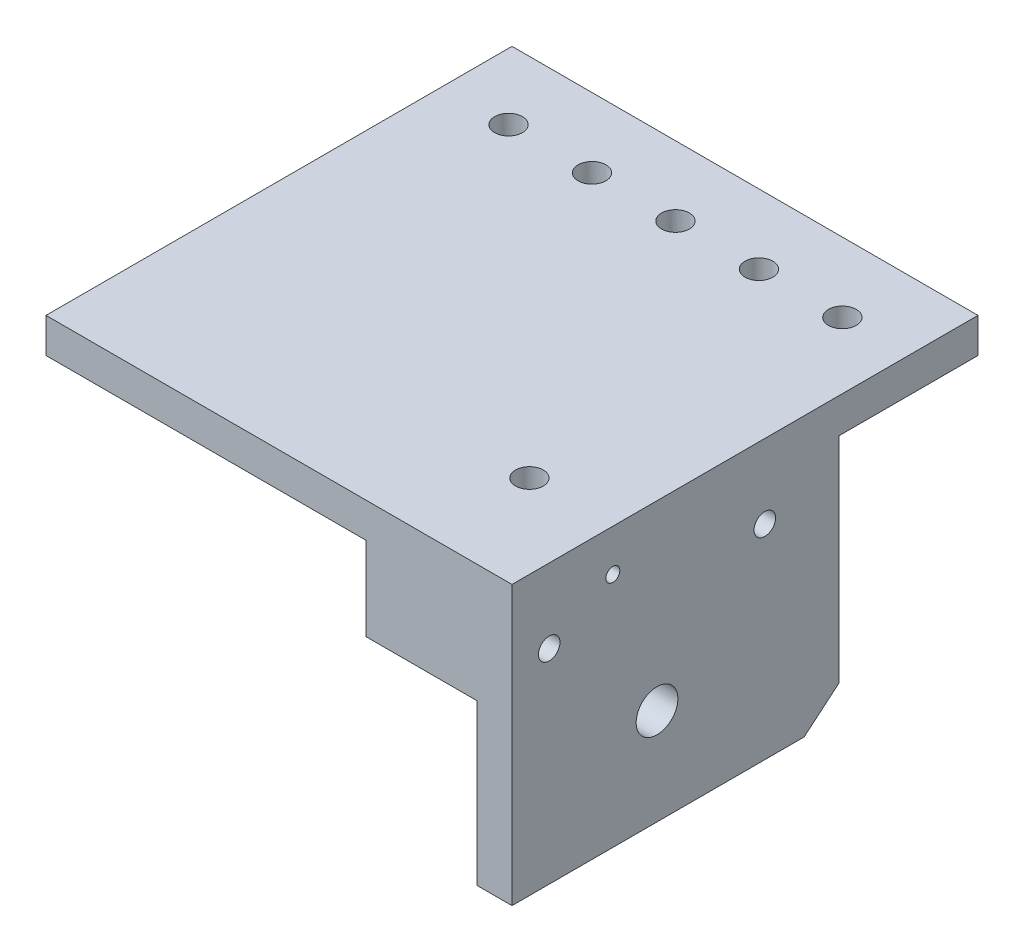
SolidWorks part; units mm, degrees
ref_plane "Front Plane" through (0, 0, 0) normal (0, 0, 1) x (1, 0, 0)
ref_plane "Top Plane" through (0, 0, 0) normal (0, 1, 0) x (1, 0, 0)
ref_plane "Right Plane" through (0, 0, 0) normal (1, 0, 0) x (0, 0, -1)
sketch "Sketch1" plane through (0, 0, 0) normal (1, 0, 0) x (0, 0, -1)
  line L0 (-15, 15) -> (-15, -25)
  line L1 (-10, -10) -> (10, -10) construction
  line L2 (-10, -10) -> (-10, 10)
  line L3 (-10, 10) -> (10, 10)
  line L4 (10, -10) -> (10, 10) construction
  line L5 (-10, -10) -> (10, 10) construction
  line L6 (-10, 10) -> (10, -10) construction
  line L7 (-15, 15) -> (10, 15)
  line L8 (10, 15) -> (10, 10)
  line L9 (-15, -25) -> (-10, -20.8045)
  line L10 (-10, -20.8045) -> (-10, -10)
  point P0 (0, 0)
  dimension "D1" = 20
  dimension "D2" = 5
  dimension "D3" = 5
  dimension "D4" = 40
  dimension "D5" = 50
extrude "Boss-Extrude1" add sketch "Sketch1" along normal blind 50
sketch "Sketch2" plane through (50, 0, 0) normal (1, 0, 0) x (0, 0, -1)
  line L0 (-15, -11.9459) -> (-10, -7.7504)
  line L6 (10, 10) -> (10, 15)
  line L7 (10, 15) -> (-15, 15)
  line L8 (-15, 15) -> (-15, -25)
  line L9 (-15, -25) -> (-10, -20.8045)
  line L10 (-10, -20.8045) -> (-10, 10)
  line L11 (-10, 10) -> (10, 10)
  line L12 (10, 10) -> (10, 15)
  line L13 (10, 15) -> (-15, 15)
  line L14 (-15, 15) -> (-15, -25)
  line L15 (-15, -25) -> (-10, -20.8045)
  line L16 (-10, -20.8045) -> (-10, 10)
  line L17 (-10, 10) -> (10, 10)
  line M8 (10, 10) -> (10, 15)
  line M9 (10, 15) -> (-15, 15)
  line M10 (-15, 15) -> (-15, -25)
  line M12 (-10, -20.8045) -> (-10, 10)
  line M13 (-10, 10) -> (10, 10)
  dimension "D2" = 10
  dimension "D1" = 0
extrude "Boss-Extrude2" add sketch "Sketch2" along normal blind 12 contours L0 M10 M12 M13 M8 M9
sketch "Sketch4" plane through (62, 0, 0) normal (1, 0, 0) x (0, 0, -1)
  line L4 (-10, -7.7504) -> (-15, -11.9459)
  line L5 (-15, -11.9459) -> (-15, -25)
  line L6 (-15, -25) -> (-10, -20.8045)
  line L7 (-10, -20.8045) -> (-10, -7.7504)
  line L8 (-10, -7.7504) -> (-15, -11.9459)
  line L9 (-15, -11.9459) -> (-15, -25)
  line L10 (-15, -25) -> (-10, -20.8045)
  line L11 (-10, -20.8045) -> (-10, -7.7504)
  line L14 (-15, 15) -> (-15, -11.9459)
  line L15 (-15, -11.9459) -> (-10, -7.7504)
  line L16 (-10, -7.7504) -> (-10, 10)
  line L17 (-10, 10) -> (10, 10)
  line L18 (10, 10) -> (10, 15)
  line L19 (10, 15) -> (-15, 15)
  line L20 (-15, 15) -> (-15, -11.9459)
  line L21 (-15, -11.9459) -> (-10, -7.7504)
  line L22 (-10, -7.7504) -> (-10, 10)
  line L23 (-10, 10) -> (10, 10)
  line L24 (10, 10) -> (10, 15)
  line L25 (10, 15) -> (-15, 15)
  line M11 (-15, 15) -> (-15, -11.9459)
  line M12 (-15, -11.9459) -> (-10, -7.7504)
  line M13 (-10, -7.7504) -> (-10, 10)
  line M14 (-10, 10) -> (10, 10)
  line M15 (10, 10) -> (10, 15)
  line M16 (10, 15) -> (-15, 15)
  dimension "D1" = 0
  dimension "D2" = 0
extrude "Boss-Extrude3" add sketch "Sketch4" along normal blind 5 contours M16 M11 M12 M13 M14 M15 | L10 L11 L9 M12
sketch "Sketch5" plane through (0, 0, 15) normal (0, 0, 1) x (1, 0, 0)
  line L0 (67, 15) -> (67, -25) construction
  line L1 (0, 15) -> (67, 15)
  line L2 (0, 15) -> (0, 10)
  line L3 (0, 10) -> (67, 10)
  line L4 (67, 15) -> (67, 10)
  line L6 (62, -25) -> (67, -25)
  line L7 (62, -25) -> (62, 10)
  line L8 (62, 10) -> (67, 10)
  line L9 (67, -25) -> (67, 10)
  line L10 (46, 10) -> (62, 10)
  line L11 (46, 10) -> (46, -2)
  line L12 (46, -2) -> (62, -2)
  line L13 (62, 10) -> (62, -2)
  line M7 (0, 15) -> (0, -25)
  line M11 (62, -11.9459) -> (62, -25)
  line M12 (62, -25) -> (67, -25)
  line M13 (67, -25) -> (67, 15)
  line M14 (67, 15) -> (0, 15)
  dimension "D1" = 5
  dimension "D2" = 12
  dimension "D3" = 16
extrude "Boss-Extrude4" add sketch "Sketch5" along normal blind 42 contours L3 M7 M13 M14 | L11 L12 L7 L3 | L7 L3 M11 M12 M13
sketch "Sketch6" plane through (67, 0, 0) normal (1, 0, 0) x (0, 0, -1)
  line L0 (-57, -25) -> (-57, 15) construction
  line L1 (-57, -25) -> (-15, -25) construction
  circle A0 centre (-36.15, -11.15) radius 3
  dimension "D1" = 20.85
  dimension "D2" = 6
  dimension "D3" = 13.85
extrude "Cut-Extrude1" cut sketch "Sketch6" against normal through all
sketch "Sketch7" plane through (62, 0, 0) normal (-1, 0, 0) x (0, 0, 1)
  circle A0 centre (36.15, -11.15) radius 12
  dimension "D1" = 24
extrude "Cut-Extrude2" cut sketch "Sketch7" along normal through all from offset 14
sketch "Sketch8" plane through (67, 0, 0) normal (1, 0, 0) x (0, 0, -1)
  line L1 (-20.65, -26.65) -> (-51.65, -26.65) construction
  line L2 (-20.65, -26.65) -> (-20.65, 4.35) construction
  line L3 (-20.65, 4.35) -> (-51.65, 4.35) construction
  line L4 (-51.65, -26.65) -> (-51.65, 4.35) construction
  line L5 (-20.65, -26.65) -> (-51.65, 4.35) construction
  line L6 (-20.65, 4.35) -> (-51.65, -26.65) construction
  circle A0 centre (-51.65, 4.35) radius 1.55
  circle A1 centre (-20.65, 4.35) radius 1.55
  point P4 (-36.15, -11.15)
  point P5 (0, 0)
  dimension "D2" = 3.1
  dimension "D1" = 15.5
extrude "Cut-Extrude3" cut sketch "Sketch8" against normal through all
sketch "Sketch9" plane through (0, 15, 0) normal (0, 1, 0) x (1, 0, 0)
  line L0 (67, -57) -> (0, -57) construction
  line L1 (46, -57) -> (46, -15) construction
  line L2 (46, -57) -> (46, -15) construction
  circle A0 centre (55, -42.5) radius 1.5
  dimension "D1" = 3
  dimension "D2" = 14.5
  dimension "D3" = 9
extrude "Cut-Extrude4" cut sketch "Sketch9" against normal blind 42
sketch "Sketch10" plane through (0, 15, 0) normal (0, 1, 0) x (1, 0, 0)
  circle A1 centre (55, -42.5) radius 2
  dimension "D1" = 4
extrude "Cut-Extrude5" cut sketch "Sketch10" against normal blind 10
sketch "Sketch11" plane through (67, 0, 0) normal (1, 0, 0) x (0, 0, -1)
  line L0 (-57, -25) -> (-57, 15) construction
  line L1 (10, 15) -> (-57, 15) construction
  circle A0 centre (-42.5, 9) radius 1
  dimension "D1" = 2
  dimension "D2" = 14.5
  dimension "D3" = 6
extrude "Cut-Extrude6" cut sketch "Sketch11" against normal through all
sketch "Sketch12" plane through (0, 15, 0) normal (0, 1, 0) x (1, 0, 0)
  line L0 (67, 0) -> (0, 0) construction
  line L1 (67, 10) -> (67, -57) construction
  line L2 (0, 10) -> (0, -57) construction
  line L3 (9.5, 0) -> (0, 10) construction
  line L5 (57.5, 0) -> (67, 10) construction
  circle A0 centre (9.5, 0) radius 2
  circle A1 centre (21.5, 0) radius 2
  circle A2 centre (33.5, 0) radius 2
  circle A3 centre (45.5, 0) radius 2
  circle A4 centre (57.5, 0) radius 2
  dimension "D1" = 4
  dimension "D3" = 12
  dimension "D4" = 12
  dimension "D5" = 12
  dimension "D6" = 12
extrude "Cut-Extrude7" cut sketch "Sketch12" against normal blind 10
sketch "Sketch13" plane through (0, 0, 10) normal (0, 0, -1) x (-1, 0, 0)
  line L0 (0, 0) -> (-67, 0) construction
  line L1 (-67, -20.8045) -> (-67, 10) construction
  line L2 (0, -20.8045) -> (0, 10) construction
  circle A0 centre (-5, 0) radius 2
  circle A1 centre (-16, 0) radius 2
  circle A2 centre (-27, 0) radius 2
  dimension "D1" = 4
  dimension "D2" = 5
  dimension "D3" = 11
  dimension "D4" = 11
extrude "Cut-Extrude8" cut sketch "Sketch13" against normal blind 10
equation "\"`0\"=7.20644"
